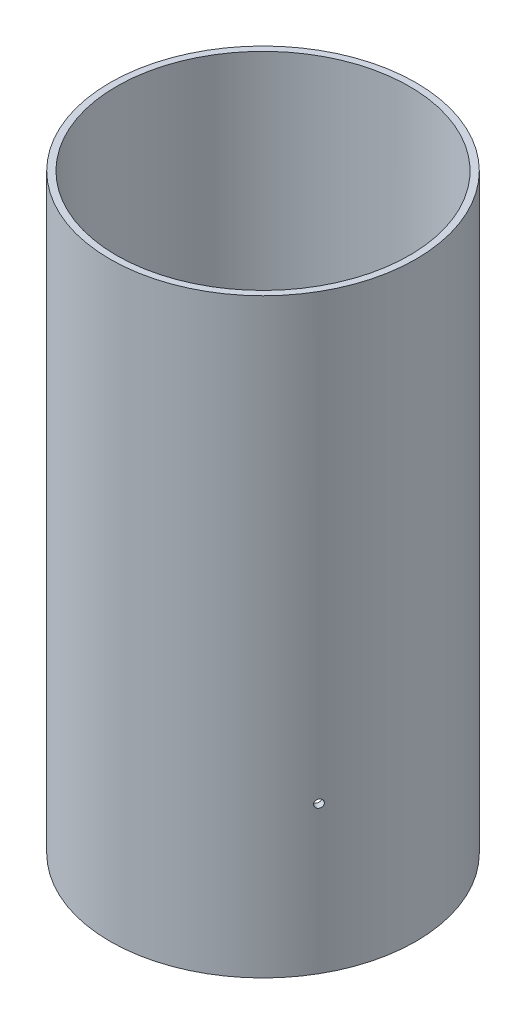
SolidWorks part; units mm, degrees
material "G12 Fiberglass"
ref_plane "Front Plane" through (0, 0, 0) normal (0, 0, 1) x (1, 0, 0)
ref_plane "Top Plane" through (0, 0, 0) normal (0, 1, 0) x (1, 0, 0)
ref_plane "Right Plane" through (0, 0, 0) normal (1, 0, 0) x (0, 0, -1)
sketch "Sketch1" plane through (0, 0, 0) normal (0, 1, 0) x (1, 0, 0)
  circle A0 centre (0, 0) radius 36.5125
  circle A1 centre (0, 0) radius 38.1381
  dimension "D1" = 73.025
  dimension "D2" = 1.6256
extrude "Boss-Extrude1" add sketch "Sketch1" along normal blind 147.32
ref_axis "Axis1" through (0, 155.0861, 0) along (0, -1, 0)
ref_plane "Shear Pin Plane" through (33.0286, 0, 19.0691) normal (0.866, 0, 0.5) x (0, -1, 0)
sketch "Sketch2" plane through (33.0286, 0, 19.0691) normal (0.866, 0, 0.5) x (0, -1, 0)
  circle A0 centre (-36.7284, 0) radius 0.9906
  dimension "D1" = 1.9812
  dimension "D2" = 36.7284
extrude "Shear Pin Cut" cut sketch "Sketch2" against normal up to next
pattern_circular "Shear Pin Pattern" count 3 over 360 about axis through (0, 155.0861, 0) along (0, -1, 0) of "Shear Pin Cut"
equation "\"D2@Sketch2\"=2.892/2"
